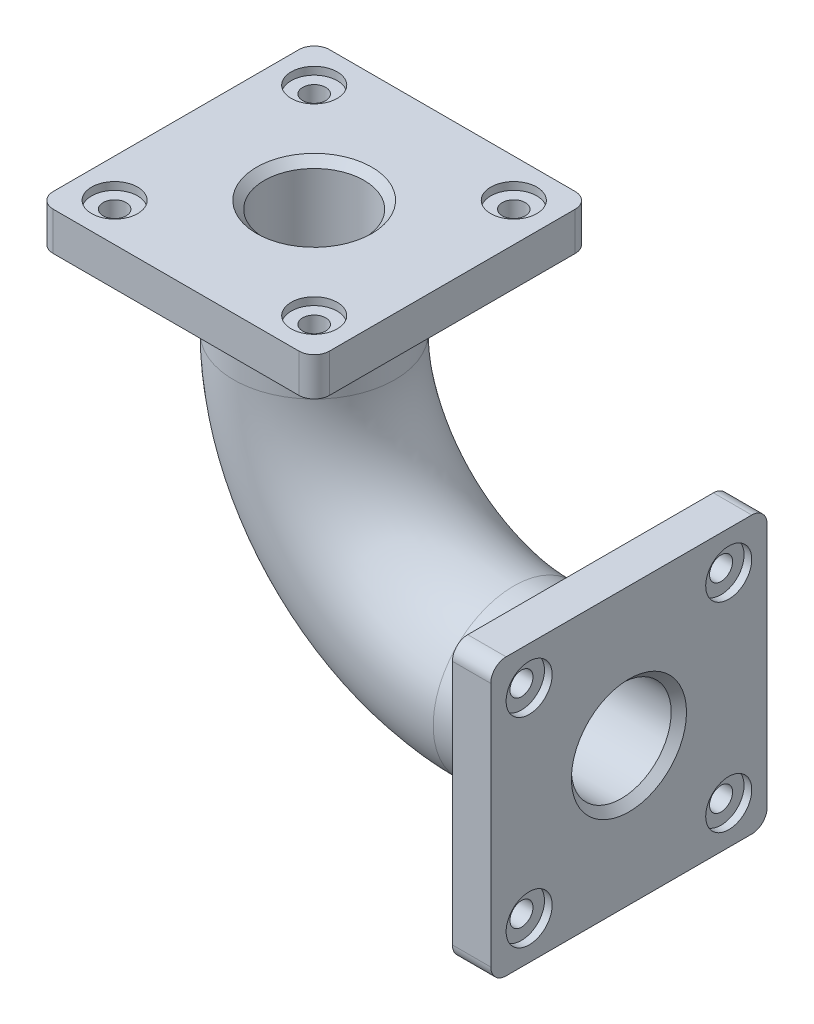
SolidWorks part; units mm, degrees
ref_plane "Front Plane" through (0, 0, 0) normal (0, 0, 1) x (1, 0, 0)
ref_plane "Top Plane" through (0, 0, 0) normal (0, 1, 0) x (1, 0, 0)
ref_plane "Right Plane" through (0, 0, 0) normal (1, 0, 0) x (0, 0, -1)
sketch "Sketch1" plane through (0, 0, 0) normal (0, 0, 1) x (1, 0, 0)
  line L0 (0, 0) -> (-150, 0)
  line L1 (-410, 260) -> (-410, 410)
  arc A0 (-150, 0) -> (-410, 260) centre (-150, 260) cw
  point P5 (-333.8478, 76.1522)
  dimension "D1" = 150
  dimension "D2" = 150
  dimension "D3" = 260
sketch "Sketch2" plane through (0, 0, 0) normal (1, 0, 0) x (0, 0, -1)
  circle A0 centre (0, 0) radius 105
  point P0 (0, 0)
  dimension "D3" = 210
sweep "Sweep-Thin1" add profiles "Sketch2" path "Sketch1" parameters "D1"=40
sketch "Sketch4" plane through (0, 0, 0) normal (1, 0, 0) x (0, 0, -1)
  line L1 (-180, 180) -> (180, 180)
  line L2 (-180, 180) -> (-180, -180)
  line L3 (-180, -180) -> (180, -180)
  line L4 (180, 180) -> (180, -180)
  line L5 (-180, 180) -> (180, -180) construction
  line L6 (-180, -180) -> (180, 180) construction
  point P0 (0, 0)
  circle M4 centre (0, 0) radius 105
  dimension "D1" = 360
  dimension "D2" = 360
extrude "Boss-Extrude1" add sketch "Sketch4" against normal blind 50 contours L4 L1 L2 L3 M4
fillet "Fillet1" radius 20 4 edges at (-25, 180, -180) (-25, -180, 180) (-25, -180, -180) (-25, 180, 180)
sketch "Sketch5" plane through (0, 410, 0) normal (0, 1, 0) x (1, 0, 0)
  line L1 (-570, 180) -> (-250, 180)
  line L2 (-590, 160) -> (-590, -160)
  line L3 (-570, -180) -> (-250, -180)
  line L4 (-230, 160) -> (-230, -160)
  line L5 (-590, 180) -> (-230, -180) construction
  line L6 (-590, -180) -> (-230, 180) construction
  arc A0 (-250, 180) -> (-230, 160) centre (-250, 160) cw
  arc A1 (-590, -160) -> (-570, -180) centre (-570, -160) ccw
  arc A2 (-570, 180) -> (-590, 160) centre (-570, 160) ccw
  arc A3 (-250, -180) -> (-230, -160) centre (-250, -160) ccw
  point P0 (-410, 0)
  point P18 (0, 0)
  point P19 (0, 0)
  point P20 (0, 0)
  circle M4 centre (-410, 0) radius 105
  dimension "D3" = 20
  dimension "D1" = 360
  dimension "D2" = 360
extrude "Boss-Extrude2" add sketch "Sketch5" against normal blind 50 contours L3 A3 L4 A0 L1 A2 L2 A1 M4
sketch "Sketch6" plane through (0, 410, 0) normal (0, 1, 0) x (1, 0, 0)
  line L1 (-540, 130) -> (-280, 130) construction
  line L2 (-540, 130) -> (-540, -130) construction
  line L3 (-540, -130) -> (-280, -130) construction
  line L4 (-280, 130) -> (-280, -130) construction
  line L5 (-540, 130) -> (-280, -130) construction
  line L6 (-540, -130) -> (-280, 130) construction
  circle A0 centre (-540, 130) radius 30
  point P0 (-410, 0)
  dimension "D3" = 60
  dimension "D1" = 260
  dimension "D2" = 260
extrude "Cut-Extrude1" cut sketch "Sketch6" against normal blind 10
sketch "Sketch7" plane through (0, 400, 0) normal (0, 1, 0) x (1, 0, 0)
  circle A0 centre (-540, 130) radius 15
  circle A1 centre (-540, 130) radius 30 construction
  dimension "D1" = 30
extrude "Cut-Extrude2" cut sketch "Sketch7" against normal up to next
pattern_circular "CirPattern1" count 4 over 360 about axis through (-410, 0, 0) along (0, 1, 0) of "Cut-Extrude2", "Cut-Extrude1"
sketch "Sketch8" plane through (0, 0, 0) normal (1, 0, 0) x (0, 0, -1)
  line L1 (-130, 130) -> (130, 130) construction
  line L2 (-130, 130) -> (-130, -130) construction
  line L3 (-130, -130) -> (130, -130) construction
  line L4 (130, 130) -> (130, -130) construction
  line L5 (-130, 130) -> (130, -130) construction
  line L6 (-130, -130) -> (130, 130) construction
  circle A0 centre (-130, 130) radius 30
  point P0 (0, 0)
  dimension "D3" = 60
  dimension "D1" = 260
  dimension "D2" = 260
extrude "Cut-Extrude4" cut sketch "Sketch8" against normal blind 10
sketch "Sketch10" plane through (-10, 0, 0) normal (1, 0, 0) x (0, 0, -1)
  circle A0 centre (-130, 130) radius 15
extrude "Cut-Extrude5" cut sketch "Sketch10" against normal up to next
pattern_circular "CirPattern2" count 4 over 360 about axis through (0, 0, 0) along (1, 0, 0) of "Cut-Extrude5", "Cut-Extrude4"
chamfer "Chamfer1" distance 10 angle 45 2 edges at (0, 0, -65) (-345, 410, 0)
